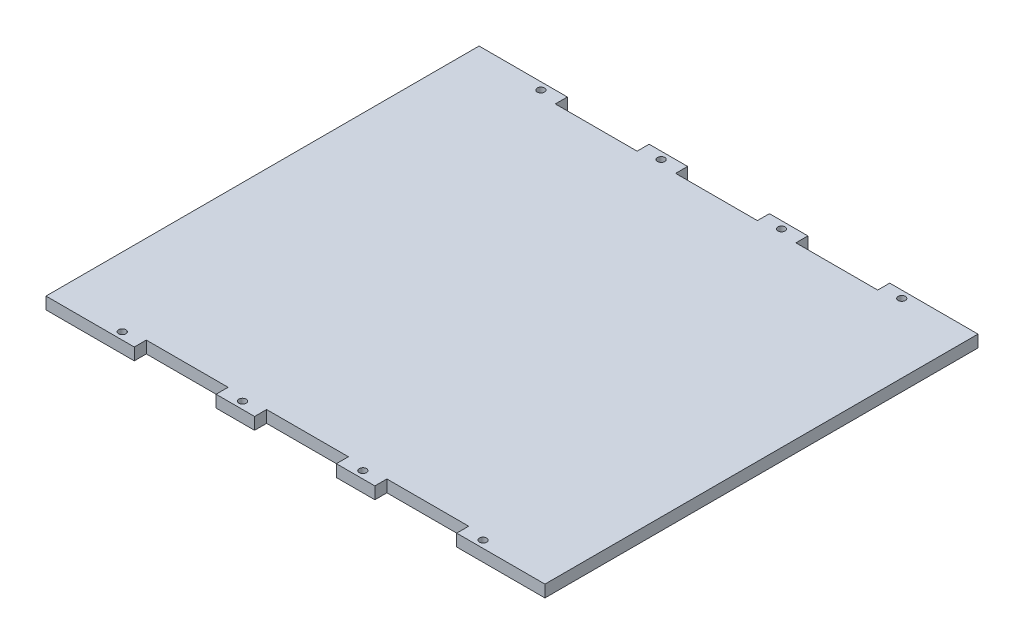
SolidWorks part; units mm, degrees
material "Trupan"
ref_plane "Alzado" through (0, 0, 0) normal (0, 0, 1) x (1, 0, 0)
ref_plane "Planta" through (0, 0, 0) normal (0, 1, 0) x (1, 0, 0)
ref_plane "Vista lateral" through (0, 0, 0) normal (1, 0, 0) x (0, 0, -1)
sketch "Croquis1" plane through (0, 0, 0) normal (0, 1, 0) x (1, 0, 0)
  line L1 (100, -90) -> (-100, -90)
  line L2 (100, -90) -> (100, 90)
  line L3 (100, 90) -> (-100, 90)
  line L4 (-100, -90) -> (-100, 90)
  line L5 (100, -90) -> (-100, 90) construction
  line L6 (100, 90) -> (-100, -90) construction
  point P0 (0, 0)
  dimension "D1" = 200
  dimension "D2" = 180
extrude "Saliente-Extruir1" add sketch "Croquis1" along normal blind 5
sketch "Croquis4" plane through (0, 5, 0) normal (0, 1, 0) x (1, 0, 0)
  line L14 (-100, 0) -> (100, 0) construction
  line L15 (-100, 90) -> (-100, -90) construction
  line L22 (100, -90) -> (100, 90) construction
  line L23 (0, -90) -> (0, 90) construction
  line L24 (-100, -90) -> (100, -90) construction
  line L25 (100, 90) -> (-100, 90) construction
  line L26 (-50, -90) -> (-50, 90) construction
  line L27 (50, 90) -> (50, -90) construction
  line L29 (-83, -90) -> (-67, -90)
  line L30 (-83, -90) -> (-83, -85)
  line L31 (-83, -85) -> (-67, -85)
  line L32 (-67, -90) -> (-67, -85)
  line L33 (-33, -90) -> (-17, -90)
  line L34 (-33, -90) -> (-33, -85)
  line L35 (-33, -85) -> (-17, -85)
  line L36 (-17, -90) -> (-17, -85)
  line L37 (-83, -90) -> (-100, -90)
  line L38 (-83, -90) -> (-83, -85)
  line L39 (-83, -85) -> (-100, -85)
  line L40 (-100, -90) -> (-100, -85)
  line L41 (-67, -85) -> (-33, -85)
  line L42 (-67, -85) -> (-67, -90)
  line L43 (-67, -90) -> (-33, -90)
  line L44 (-33, -85) -> (-33, -90)
  line L45 (-17, -85) -> (0, -85)
  line L46 (-17, -85) -> (-17, -90)
  line L47 (-17, -90) -> (0, -90)
  line L48 (0, -85) -> (0, -90)
  point P27 (-75, -90)
  point P28 (-25, -90)
  line M11 (-100, 90) -> (-100, -90)
  line M12 (-100, -90) -> (100, -90)
  dimension "D1" = 50
  dimension "D2" = 50
  dimension "D3" = 5
  dimension "D5" = 16
  dimension "D6" = 16
  dimension "D7" = 25
  dimension "D8" = 25
extrude "Cortar-Extruir4" cut sketch "Croquis4" against normal through all contours L30 L39 M11 M12 | L41 L32 L34 M12 | L48 L45 L36 M12
mirror "Simetría2" about plane through (0, 0, 0) normal (1, 0, 0) of "Cortar-Extruir4"
mirror "Simetría3" about plane through (0, 0, 0) normal (0, 0, 1) of "Simetría2", "Cortar-Extruir4"
sketch "Croquis5" plane through (0, 5, 0) normal (0, 1, 0) x (1, 0, 0)
  line L1 (-67, -90) -> (-67, -85) construction
  line L3 (-83, -90) -> (-67, -90) construction
  line L4 (-17, -90) -> (-17, -85) construction
  line L5 (-33, -90) -> (-17, -90) construction
  line L6 (33, -90) -> (33, -85) construction
  line L7 (17, -90) -> (33, -90) construction
  line L8 (67, -90) -> (83, -90) construction
  line L9 (83, -90) -> (83, -85) construction
  circle A0 centre (-75, -87) radius 1.5
  circle A1 centre (-25, -87) radius 1.5
  circle A2 centre (25, -87) radius 1.5
  circle A3 centre (75, -87) radius 1.5
  dimension "D9" = 3
  dimension "D10" = 3
  dimension "D11" = 3
  dimension "D12" = 3
  dimension "D1" = 8
  dimension "D2" = 3
  dimension "D3" = 8
  dimension "D4" = 3
  dimension "D5" = 8
  dimension "D6" = 3
  dimension "D7" = 3
  dimension "D8" = 8
extrude "Cortar-Extruir5" cut sketch "Croquis5" against normal through all
mirror "Simetría4" about plane through (0, 0, 0) normal (0, 0, 1) of "Cortar-Extruir5"
sketch "Croquis6" plane through (0, 5, 0) normal (0, 1, 0) x (1, 0, 0)
  line L1 (83, 90) -> (100, 90)
  line L2 (83, 90) -> (83, 85)
  line L3 (83, 85) -> (100, 85)
  line L4 (100, 90) -> (100, 85)
extrude "Saliente-Extruir3" add sketch "Croquis6" against normal through all
mirror "Simetría5" about plane through (0, 0, 0) normal (1, 0, 0) of "Saliente-Extruir3"
mirror "Simetría6" about plane through (0, 0, 0) normal (0, 0, 1) of "Simetría5", "Saliente-Extruir3"
sketch "Croquis9" plane through (0, 5, 0) normal (0, 1, 0) x (1, 0, 0)
  line L1 (100, 90) -> (103.69, 90)
  line L2 (100, 90) -> (100, -90)
  line L3 (100, -90) -> (103.69, -90)
  line L4 (103.69, 90) -> (103.69, -90)
  dimension "D1" = 3.69
  dimension "D2" = 180
extrude "Saliente-Extruir7" add sketch "Croquis9" against normal blind 5
mirror "Simetría7" about plane through (0, 0, 0) normal (1, 0, 0) of "Saliente-Extruir7"
